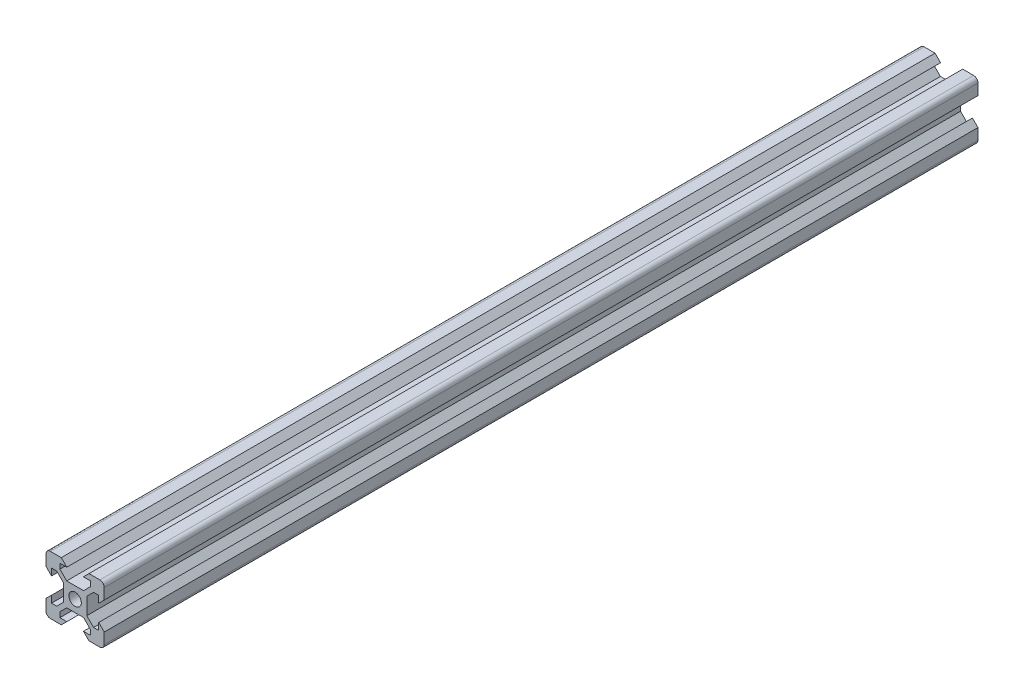
SolidWorks part; units mm, degrees
material "2219-T81"
ref_plane "Front Plane" through (0, 0, 0) normal (0, 0, 1) x (1, 0, 0)
ref_plane "Top Plane" through (0, 0, 0) normal (0, 1, 0) x (1, 0, 0)
ref_plane "Right Plane" through (0, 0, 0) normal (1, 0, 0) x (0, 0, -1)
sketch "Sketch1" plane through (0, 0, 0) normal (0, 0, 1) x (1, 0, 0)
  line L0 (15.6876, 55.3211) -> (115.0437, 55.3211) construction
  line L1 (8.1, 5.225) -> (8.1, 2.85)
  line L2 (-8.5, 10) -> (-4.75, 10)
  line L3 (-10, 8.5) -> (-10, 4.75)
  line L4 (-8.5, -10) -> (-4.75, -10)
  line L5 (10, 8.5) -> (10, 4.75)
  line L6 (6.325, 5.225) -> (4, 2.9)
  line L7 (-8.1, -2.85) -> (-8.1, -5.225)
  line L8 (-2.9, 4) -> (2.9, 4)
  line L9 (-4, 2.9) -> (-4, -2.9)
  line L10 (-2.9, -4) -> (2.9, -4)
  line L11 (4, 2.9) -> (4, -2.9)
  line L12 (2.85, -8.1) -> (5.225, -8.1)
  line L13 (-5.225, -8.1) -> (-2.85, -8.1)
  line L14 (5.225, 6.325) -> (2.9, 4)
  line L17 (-10, 4.75) -> (-8.1, 2.85)
  line L20 (4.75, -10) -> (8.5, -10)
  line L22 (-10, -4.75) -> (-10, -8.5)
  line L23 (10, -4.75) -> (10, -8.5)
  line L24 (-10, -4.75) -> (-8.1, -2.85)
  line L25 (-4.75, -10) -> (-2.85, -8.1)
  line L26 (4.75, -10) -> (2.85, -8.1)
  line L27 (10, -4.75) -> (8.1, -2.85)
  line L28 (10, 4.75) -> (8.1, 2.85)
  line L29 (-4.75, 10) -> (-2.85, 8.1)
  line L30 (4.75, 10) -> (2.85, 8.1)
  line L31 (8.1, -2.85) -> (8.1, -5.225)
  line L32 (6.325, -5.225) -> (8.1, -5.225)
  line L33 (5.225, -6.325) -> (5.225, -8.1)
  line L34 (4.75, 10) -> (8.5, 10)
  line L35 (2.85, 8.1) -> (5.225, 8.1)
  line L36 (10, -10) -> (10.975, -10.975) construction
  line L37 (-5.225, 8.1) -> (-2.85, 8.1)
  line L38 (-8.1, -5.225) -> (-6.325, -5.225)
  line L39 (-5.225, 6.325) -> (-2.9, 4)
  line L40 (-8.1, 5.225) -> (-8.1, 2.85)
  line L41 (-5.225, -6.325) -> (-5.225, -8.1)
  line L42 (-6.325, 5.225) -> (-4, 2.9)
  line L46 (-8.1, 5.225) -> (-6.325, 5.225)
  line L47 (-5.225, 8.1) -> (-5.225, 6.325)
  line L52 (8.1, 5.225) -> (6.325, 5.225)
  line L53 (5.225, 8.1) -> (5.225, 6.325)
  line L63 (4, -2.9) -> (6.325, -5.225)
  line L66 (2.9, -4) -> (5.225, -6.325)
  line L67 (-2.9, -4) -> (-5.225, -6.325)
  line L70 (-4, -2.9) -> (-6.325, -5.225)
  arc A0 (-8.5, -10) -> (-10, -8.5) centre (-8.5, -8.5) cw
  arc A1 (8.5, -10) -> (10, -8.5) centre (8.5, -8.5) ccw
  arc A2 (10, 8.5) -> (8.5, 10) centre (8.5, 8.5) ccw
  arc A3 (-8.5, 10) -> (-10, 8.5) centre (-8.5, 8.5) ccw
  circle A4 centre (0, 0) radius 2.125
  point P2 (0, 0)
  point P8 (0, 0)
  point P14 (-10, -10)
  point P20 (0, 0)
  point P49 (10, 10)
  point P52 (-10, 10)
  dimension "D3" = 1.5
  dimension "D4" = 4.25
  dimension "D1" = 20
  dimension "D2" = 20
  dimension "D13" = 5.25
  dimension "D14" = 5.25
  dimension "D15" = 90
  dimension "D16" = 5.25
  dimension "D17" = 5.25
  dimension "D18" = 5.25
  dimension "D19" = 5.25
  dimension "D20" = 5.25
  dimension "D21" = 5.25
  dimension "D22" = 90
  dimension "D23" = 90
  dimension "D24" = 90
  dimension "D25" = 2.85
  dimension "D26" = 2.85
  dimension "D27" = 2.85
  dimension "D28" = 2.85
extrude "Boss-Extrude1" add sketch "Sketch1" along normal blind 300
